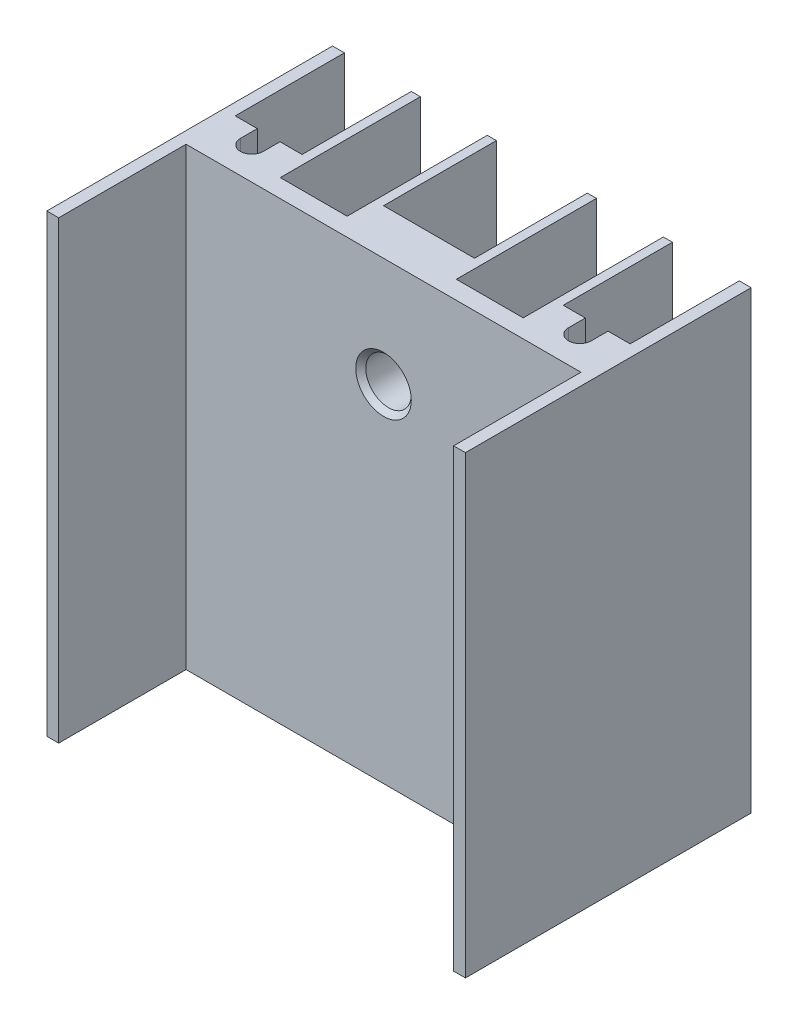
SolidWorks part; units mm, degrees
ref_plane "Front" through (0, 0, 0) normal (0, 0, 1) x (1, 0, 0)
ref_plane "Top" through (0, 0, 0) normal (0, 1, 0) x (1, 0, 0)
ref_plane "Right" through (0, 0, 0) normal (1, 0, 0) x (0, 0, -1)
sketch "Sketch1" plane through (0, 0, 0) normal (0, 1, 0) x (1, 0, 0)
  line L0 (0, 8.7) -> (0, 0) construction
  line L1 (-11.5, 8.7) -> (-10.85, 8.7)
  line L2 (-11.5, 8.7) -> (-11.5, -7)
  line L3 (-11.5, -7) -> (-10.85, -7)
  line L4 (11.5, 8.7) -> (11.5, -7)
  line L5 (0, 0) -> (13.8686, 0) construction
  line L6 (-10.85, 0) -> (10.85, 0)
  line L7 (10.85, 0) -> (10.85, -7)
  line L8 (-10.85, 0) -> (-10.85, -7)
  line L9 (10.85, -7) -> (11.5, -7)
  line L10 (-2.5, 8.7) -> (-2.5, 2.5)
  line L11 (-2.5, 2.5) -> (2.5, 2.5)
  line L12 (2.5, 2.5) -> (2.5, 8.7)
  line L13 (2.5, 8.7) -> (3, 8.7)
  line L14 (3, 8.7) -> (3, 1)
  line L15 (3, 1) -> (6.675, 1)
  line L16 (6.675, 1) -> (6.675, 8.7)
  line L17 (6.675, 8.7) -> (7.175, 8.7)
  line L18 (7.175, 8.7) -> (7.175, 2.7)
  line L19 (7.175, 2.7) -> (8.3875, 2.7)
  line L20 (8.3875, 2.7) -> (8.3875, 1.775)
  line L21 (-3, 8.7) -> (-3, 1)
  line L22 (9.6375, 1.775) -> (9.6375, 2.7)
  line L23 (9.6375, 2.7) -> (10.85, 2.7)
  line L24 (10.85, 2.7) -> (10.85, 8.7)
  line L25 (10.85, 8.7) -> (11.5, 8.7)
  line L26 (10.85, 8.7) -> (7.175, 8.7) construction
  line L27 (6.675, 8.7) -> (3, 8.7) construction
  line L28 (9.0125, 1.15) -> (9.0125, 8.7) construction
  line L29 (-3, 1) -> (-6.675, 1)
  line L30 (-6.675, 1) -> (-6.675, 8.7)
  line L31 (-7.175, 8.7) -> (-7.175, 2.7)
  line L32 (-7.175, 2.7) -> (-8.3875, 2.7)
  line L33 (-8.3875, 2.7) -> (-8.3875, 1.775)
  line L34 (-9.6375, 1.775) -> (-9.6375, 2.7)
  line L35 (-9.6375, 2.7) -> (-10.85, 2.7)
  line L36 (-10.85, 2.7) -> (-10.85, 8.7)
  line L37 (-3, 8.7) -> (-2.5, 8.7)
  line L38 (-7.175, 8.7) -> (-6.675, 8.7)
  arc A0 (8.3875, 1.775) -> (9.6375, 1.775) centre (9.0125, 1.775) ccw
  arc A1 (-8.3875, 1.775) -> (-9.6375, 1.775) centre (-9.0125, 1.775) cw
  dimension "D1" = 23
  dimension "D2" = 15.7
  dimension "D3" = 7
  dimension "D4" = 0.65
  dimension "D5" = 5
  dimension "D6" = 2.5
  dimension "D7" = 1
  dimension "D8" = 0.5
  dimension "D9" = 2.7
  dimension "D10" = 1.15
  dimension "D11" = 1.25
extrude "Boss-Extrude1" add sketch "Sketch1" along normal blind 25
hole_wizard "M3 Tapped Hole1" positions "Sketch3" profile "Sketch2" tap size "M3" standard "ISO" end condition up to next
sketch "Sketch3" plane through (0, 0, 0) normal (0, 0, 1) x (1, 0, 0)
  line L0 (-10.85, 25) -> (10.85, 25) construction
  point P0 (0, 19)
  dimension "D1" = 6
sketch "Sketch2" plane through (0, 19, 0) normal (1, 0, 0) x (0, -1, 0)
  line L0 (0, 0) -> (0, 2.5)
  line L1 (0, 2.5) -> (1.25, 2.5)
  line L2 (1.25, 2.5) -> (1.25, 0.275)
  line L3 (1.25, 0.275) -> (1.525, 0)
  line L5 (1.525, 0) -> (0, 0)
  line L6 (-1.25, 0.275) -> (-1.525, 0) construction
  line L11 (0, -6.35) -> (0, 107.95) construction
  dimension "Thru Tap Drill Dia." = 2.5
  dimension "Thru Tap Drill Depth" = 2.5
  dimension "Near C'Sink Dia." = 3.05
  dimension "Near C'Sink Angle" = 90
cosmetic thread "Hole Thread1" parameters "D2"=3
